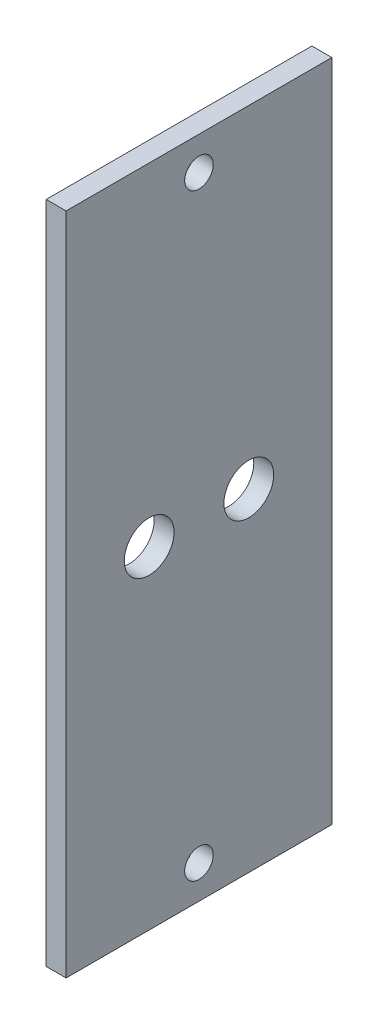
SolidWorks part; units mm, degrees
ref_plane "Front Plane" through (0, 0, 0) normal (0, 0, 1) x (1, 0, 0)
ref_plane "Top Plane" through (0, 0, 0) normal (0, 1, 0) x (1, 0, 0)
ref_plane "Right Plane" through (0, 0, 0) normal (1, 0, 0) x (0, 0, -1)
sketch "Sketch1" plane through (0, 0, 0) normal (1, 0, 0) x (0, 0, -1)
  line L0 (20, 100) -> (20, 0) construction
  line L1 (0, 0) -> (40, 0)
  line L2 (0, 0) -> (0, 100)
  line L3 (0, 100) -> (40, 100)
  line L4 (40, 0) -> (40, 100)
  line L5 (0, 50) -> (40, 50) construction
  circle A0 centre (20, 95) radius 2.15
  circle A1 centre (20, 5) radius 2.15
  circle A2 centre (12.5, 50) radius 3.75
  circle A3 centre (27.5, 50) radius 3.75
  point P15 (0, 0)
  point P18 (0, 0)
  dimension "D3" = 4.3
  dimension "D8" = 7.5
  dimension "D9" = 7.5
  dimension "D4" = 4.3
  dimension "D1" = 100
  dimension "D2" = 40
  dimension "D5" = 5
  dimension "D6" = 5
  dimension "D10" = 15
  dimension "D11" = 7.5
extrude "Boss-Extrude2" add sketch "Sketch1" along normal blind 3
equation "\"D9@Sketch1\"=\"D8@Sketch1\""
equation "\"D4@Sketch1\"=\"D3@Sketch1\""
